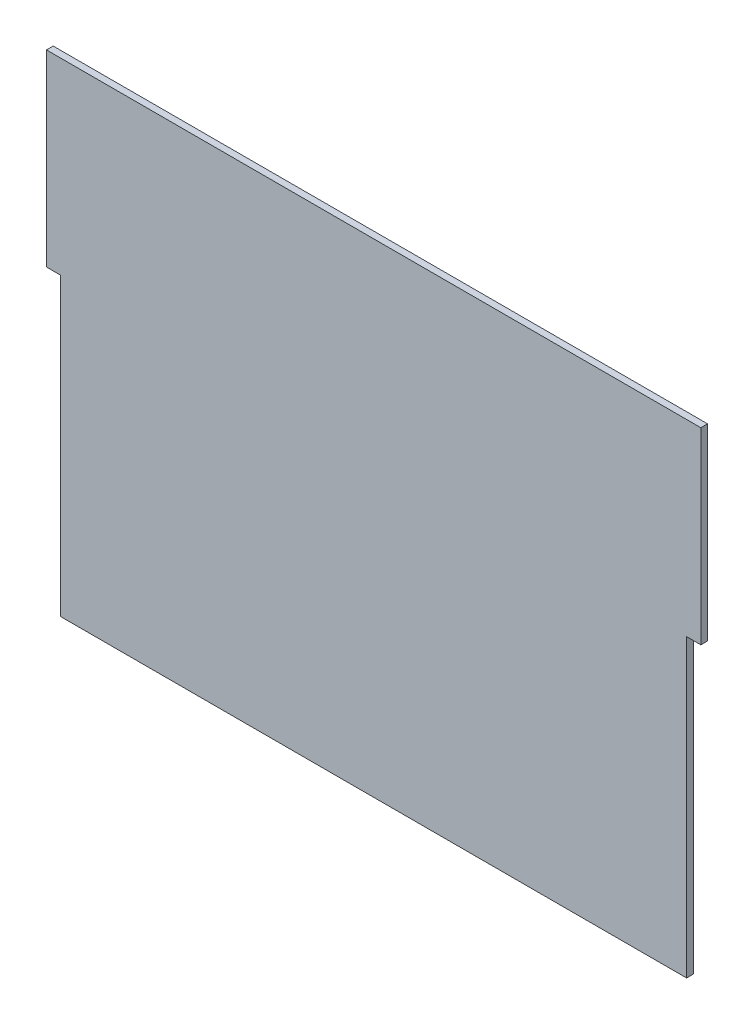
SolidWorks part; units mm, degrees
ref_plane "Front Plane" through (0, 0, 0) normal (0, 0, 1) x (1, 0, 0)
ref_plane "Top Plane" through (0, 0, 0) normal (0, 1, 0) x (1, 0, 0)
ref_plane "Right Plane" through (0, 0, 0) normal (1, 0, 0) x (0, 0, -1)
sketch "Sketch1" plane through (0, 0, 0) normal (0, 0, 1) x (1, 0, 0)
  line L0 (-146.05, 107.95) -> (146.05, 107.95)
  line L1 (146.05, 107.95) -> (146.05, 95.25)
  line L2 (146.05, 95.25) -> (139.7, 95.25)
  line L3 (139.7, 95.25) -> (139.7, -107.95)
  line L4 (139.7, -107.95) -> (-139.7, -107.95)
  line L5 (-139.7, -107.95) -> (-139.7, 95.25)
  line L6 (-139.7, 95.25) -> (-146.05, 95.25)
  line L7 (-146.05, 95.25) -> (-146.05, 107.95)
  line L8 (0, 107.95) -> (0, -107.95) construction
  line L10 (-146.05, 95.25) -> (-139.7, 95.25)
  line L11 (-146.05, 95.25) -> (-146.05, 24.003)
  line L12 (-146.05, 24.003) -> (-139.7, 24.003)
  line L13 (-139.7, 95.25) -> (-139.7, 24.003)
  line L14 (146.05, 95.25) -> (139.7, 95.25)
  line L15 (146.05, 95.25) -> (146.05, 24.003)
  line L16 (146.05, 24.003) -> (139.7, 24.003)
  line L17 (139.7, 95.25) -> (139.7, 24.003)
  point P10 (0, 0)
  dimension "D1" = 203.2
  dimension "D2" = 279.4
  dimension "D3" = 6.35
  dimension "D4" = 12.7
  dimension "D5" = 71.247
extrude "Boss-Extrude1" add sketch "Sketch1" along normal blind 2.9972 contours L8 L0 L7 L6 L5 L4 | L11 L12 L5 L6 | L0 L8 L4 L3 L2 L1 | L16 L15 L2 L3
equation "\"wallthickness\"= .118in"
equation "\"floorThickness\"= .220in"
equation "\"D1@Boss-Extrude1\"=\"wallthickness\""
